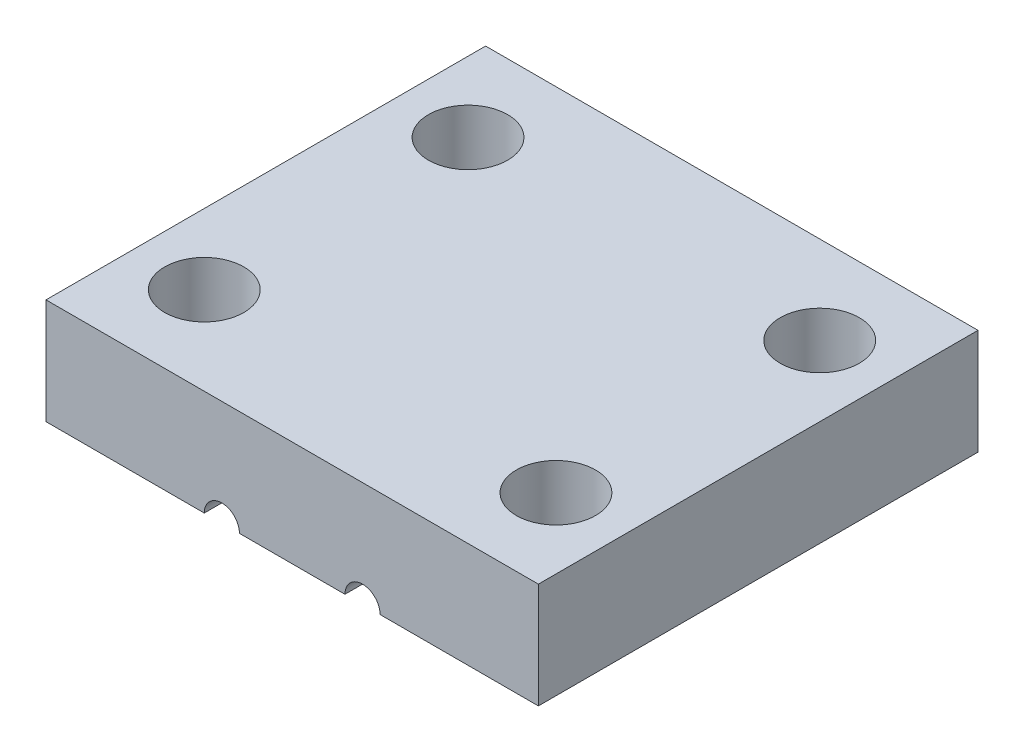
SolidWorks part; units mm, degrees
ref_plane "Front Plane" through (0, 0, 0) normal (0, 0, 1) x (1, 0, 0)
ref_plane "Top Plane" through (0, 0, 0) normal (0, 1, 0) x (1, 0, 0)
ref_plane "Right Plane" through (0, 0, 0) normal (1, 0, 0) x (0, 0, -1)
sketch "Sketch1" plane through (0, 0, 0) normal (0, 0, 1) x (1, 0, 0)
  line L0 (-14, 0) -> (14, 0)
  line L1 (-14, 0) -> (-14, 6)
  line L2 (-14, 6) -> (14, 6)
  line L3 (14, 6) -> (14, 0)
  dimension "D1" = 28
  dimension "D2" = 6
extrude "Boss-Extrude1" add sketch "Sketch1" along normal mid plane 25
sketch "Sketch2" plane through (0, 0, 12.5) normal (0, 0, 1) x (1, 0, 0)
  line L0 (-14, 0) -> (14, 0) construction
  line L1 (-4, 0) -> (4, 0) construction
  circle A0 centre (-4, 0) radius 1
  circle A1 centre (4, 0) radius 1
  dimension "D1" = 8
  dimension "D2" = 2
extrude "Cut-Extrude1" cut sketch "Sketch2" against normal blind 435
sketch "Sketch3" plane through (0, 6, 0) normal (0, 1, 0) x (1, 0, 0)
  line L1 (10, 7.5) -> (-10, 7.5) construction
  line L2 (10, 7.5) -> (10, -7.5) construction
  line L3 (10, -7.5) -> (-10, -7.5) construction
  line L4 (-10, 7.5) -> (-10, -7.5) construction
  line L5 (10, 7.5) -> (-10, -7.5) construction
  line L6 (10, -7.5) -> (-10, 7.5) construction
  circle A0 centre (-10, 7.5) radius 2.25
  circle A1 centre (-10, -7.5) radius 2.25
  circle A2 centre (10, -7.5) radius 2.25
  circle A3 centre (10, 7.5) radius 2.25
  point P0 (0, 0)
  dimension "D3" = 4.5
  dimension "D1" = 15
  dimension "D2" = 20
extrude "Cut-Extrude2" cut sketch "Sketch3" against normal through all
